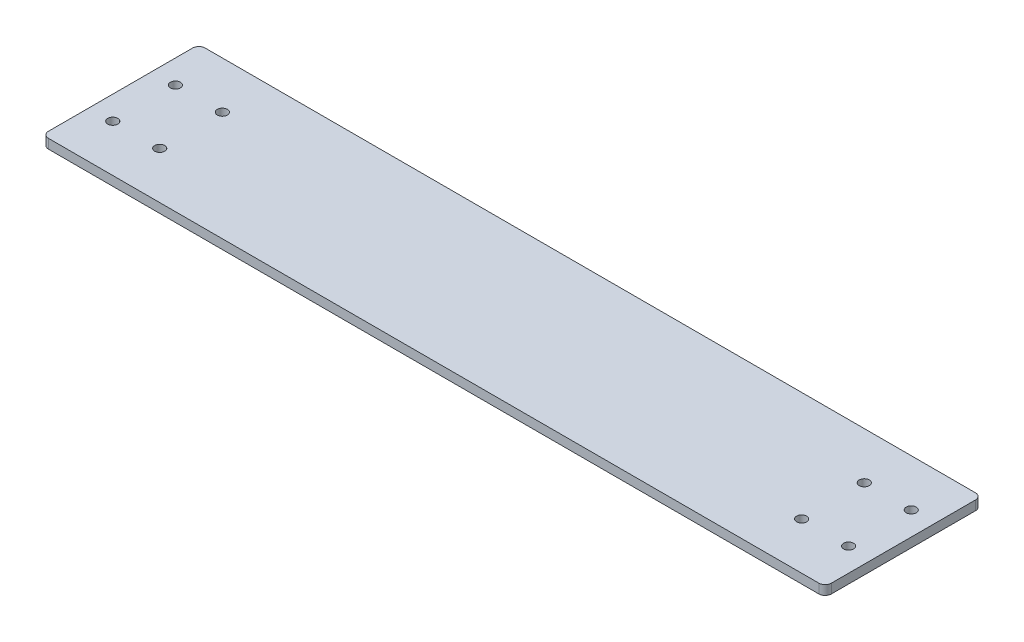
SolidWorks part; units mm, degrees
material "Thornel Mat VMA"
ref_plane "前视基准面" through (0, 0, 0) normal (0, 0, 1) x (1, 0, 0)
ref_plane "上视基准面" through (0, 0, 0) normal (0, 1, 0) x (1, 0, 0)
ref_plane "右视基准面" through (0, 0, 0) normal (1, 0, 0) x (0, 0, -1)
other "Configuration Table"
sketch "草图1" plane through (0, 0, 0) normal (0, 1, 0) x (1, 0, 0)
  line L1 (-125, 25) -> (125, 25)
  line L2 (-125, 25) -> (-125, -25)
  line L3 (-125, -25) -> (125, -25)
  line L4 (125, 25) -> (125, -25)
  line L5 (-125, 25) -> (125, -25) construction
  line L6 (-125, -25) -> (125, 25) construction
  point P0 (0, 0)
  dimension "D1" = 250
  dimension "D2" = 50
extrude "凸台-拉伸1" add sketch "草图1" along normal blind 3
sketch "草图3" plane through (0, 3, 0) normal (0, 1, 0) x (1, 0, 0)
  line L0 (-125, 0) -> (-99.5003, 0) construction
  line L1 (-125, 25) -> (-125, -25) construction
  line L2 (0, 0) -> (0, 68.6752) construction
  line L3 (-110, 25) -> (-110, 3.1789) construction
  line L4 (125, 25) -> (-125, 25) construction
  circle A0 centre (-117.5, 10) radius 1.6
  circle A1 centre (-102.5, 10) radius 1.6
  circle A2 centre (-102.5, -10) radius 1.6
  circle A3 centre (-117.5, -10) radius 1.6
  circle A4 centre (117.5, -10) radius 1.6
  circle A5 centre (102.5, 10) radius 1.6
  circle A6 centre (117.5, 10) radius 1.6
  circle A7 centre (102.5, -10) radius 1.6
  dimension "D1" = 3.2
  dimension "D5" = 15
  dimension "D4" = 20
  dimension "D6" = 15
  dimension "D2" = 2
  dimension "D3" = 2
extrude "切除-拉伸1" cut sketch "草图3" against normal up to next
sketch "草图4" plane through (0, 3, 0) normal (0, -1, 0) x (1, 0, 0)
  circle A0 centre (-117.5, 10) radius 1.6 construction
  circle A1 centre (-117.5, -10) radius 1.6 construction
  circle A2 centre (-102.5, 10) radius 1.6 construction
  circle A3 centre (-102.5, -10) radius 1.6 construction
  circle A4 centre (-117.5, 10) radius 1.6
  circle A5 centre (-117.5, -10) radius 1.6
  circle A6 centre (-102.5, 10) radius 1.6
  circle A7 centre (-102.5, -10) radius 1.6
fillet "圆角1" radius 2 4 edges at (125, 1.5, -25) (125, 1.5, 25) (-125, 1.5, 25) (-125, 1.5, -25)
